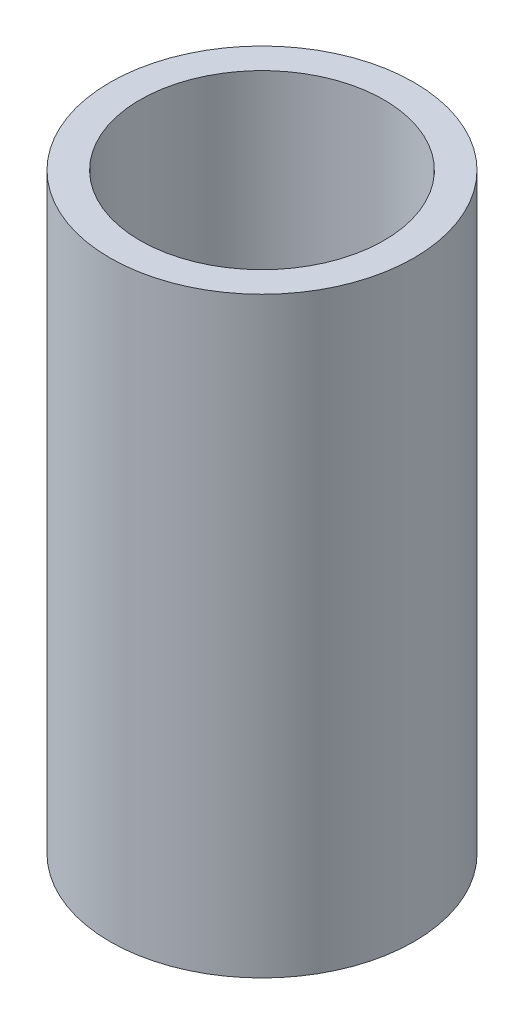
SolidWorks part; units mm, degrees
ref_plane "Front" through (0, 0, 0) normal (0, 0, 1) x (1, 0, 0)
ref_plane "Top" through (0, 0, 0) normal (0, 1, 0) x (1, 0, 0)
ref_plane "Right" through (0, 0, 0) normal (1, 0, 0) x (0, 0, -1)
sketch "Sketch1" plane through (0, 0, 0) normal (0, 1, 0) x (1, 0, 0)
  line L0 (0, 7.575) -> (0, 6.075) construction
  circle A0 centre (0, 0) radius 7.575
  circle A1 centre (0, 0) radius 6.075
  dimension "D1" = 12.15
  dimension "D2" = 1.5
extrude "Boss-Extrude1" add sketch "Sketch1" along normal blind 29.5
